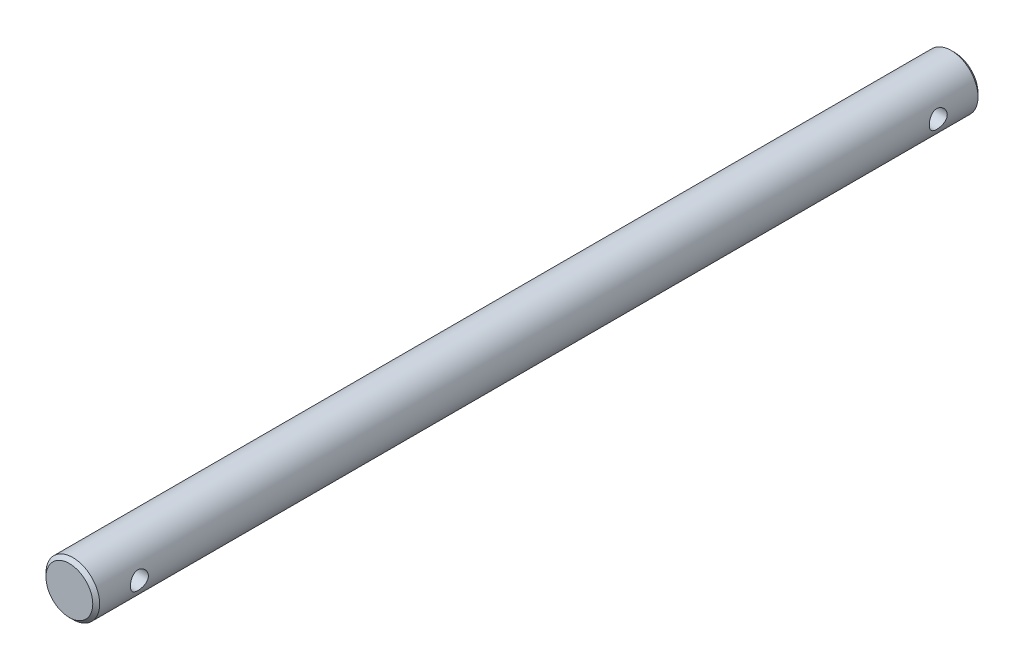
SolidWorks part; units mm, degrees
ref_plane "Front" through (0, 0, 0) normal (0, 0, 1) x (1, 0, 0)
ref_plane "Top" through (0, 0, 0) normal (0, 1, 0) x (1, 0, 0)
ref_plane "Right" through (0, 0, 0) normal (1, 0, 0) x (0, 0, -1)
sketch "Sketch1" plane through (0, 0, 0) normal (0, 0, 1) x (1, 0, 0)
  circle A0 centre (0, 0) radius 3.9497
  dimension "D1" = 7.8994
extrude "Boss-Extrude1" add sketch "Sketch1" along normal blind 130.175
ref_plane "Plane1" through (3.9497, 0, 0) normal (1, 0, 0) x (0, 0, -1)
hole_wizard "#37 (0.104) Diameter Hole1" positions "Sketch3" profile "Sketch4" hole size "#37" standard "ANSI Inch" end condition through all
sketch "Sketch3" plane through (3.9497, 0, 0) normal (1, 0, 0) x (0, 0, -1)
  line L0 (-130.175, 3.9497) -> (-130.175, -3.9497) construction
  point P0 (-6.35, 0)
  point P2 (-123.825, 0)
  point P8 (0, 0)
  point P9 (0, 0)
  dimension "D1" = 6.35
  dimension "D2" = 6.35
sketch "Sketch4" plane through (3.9497, 0, 6.35) normal (0, 1, 0) x (0, 0, -1)
  line L0 (0, 0) -> (0, 7.8994)
  line L1 (0, 7.8994) -> (1.3208, 7.8994)
  line L2 (1.3208, 7.8994) -> (1.3208, 0)
  line L5 (1.3208, 0) -> (0, 0)
  line L11 (0, -6.35) -> (0, 107.95) construction
  dimension "Thru Hole Dia." = 2.6416
  dimension "Thru Hole Depth" = 7.8994
chamfer "Chamfer1" distance 0.508 angle 45 2 edges at (3.9497, 0, 0) (3.9497, 0, 130.175)
